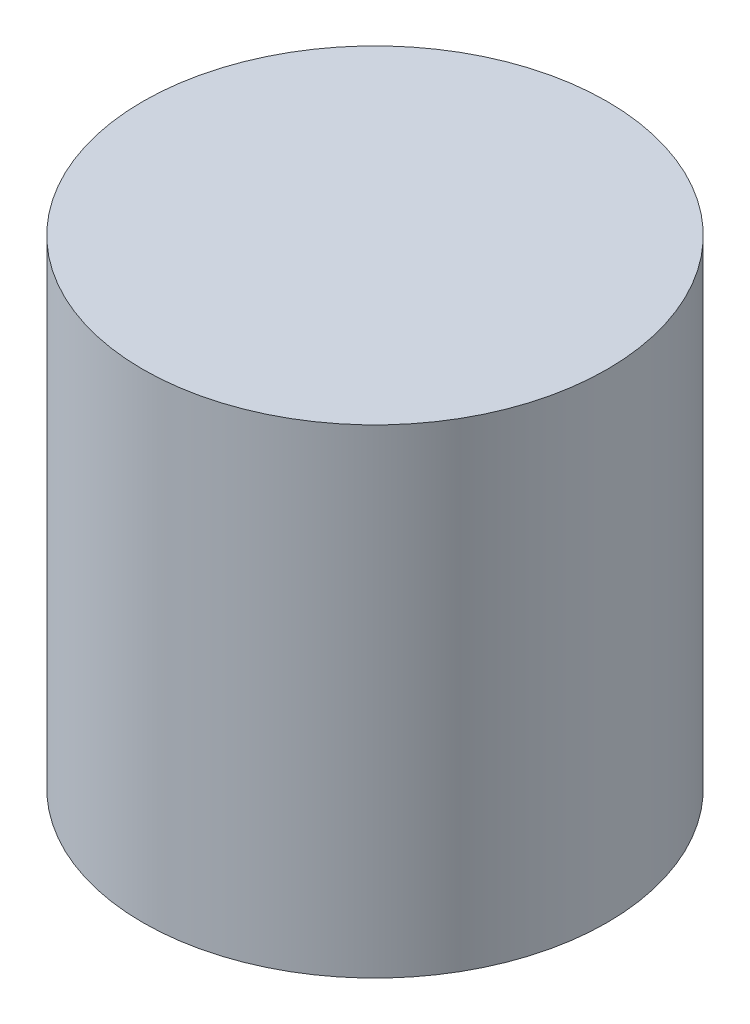
SolidWorks part; units mm, degrees
ref_plane "Спереди" through (0, 0, 0) normal (0, 0, 1) x (1, 0, 0)
ref_plane "Сверху" through (0, 0, 0) normal (0, 1, 0) x (1, 0, 0)
ref_plane "Справа" through (0, 0, 0) normal (1, 0, 0) x (0, 0, -1)
sketch "Эскиз1" plane through (0, 0, 0) normal (0, 1, 0) x (1, 0, 0)
  circle A0 centre (0, 0) radius 10
  dimension "D1" = 20
extrude "Бобышка-Вытянуть1" add sketch "Эскиз1" against normal blind 20.64
ref_plane "face_for_mating" through (0, 0, 0) normal (0, 1, 0) x (-1, 0, 0)
ref_plane "face_for_horizont" through (0, -20.64, 0) normal (0, -1, 0) x (1, 0, 0)
equation "\"H\"=7+10.26+3.38"
equation "\"D\"=20"
equation "\"D1@Эскиз1\" = \"D\""
equation "\"D1@Бобышка-Вытянуть1\" = \"H\""
